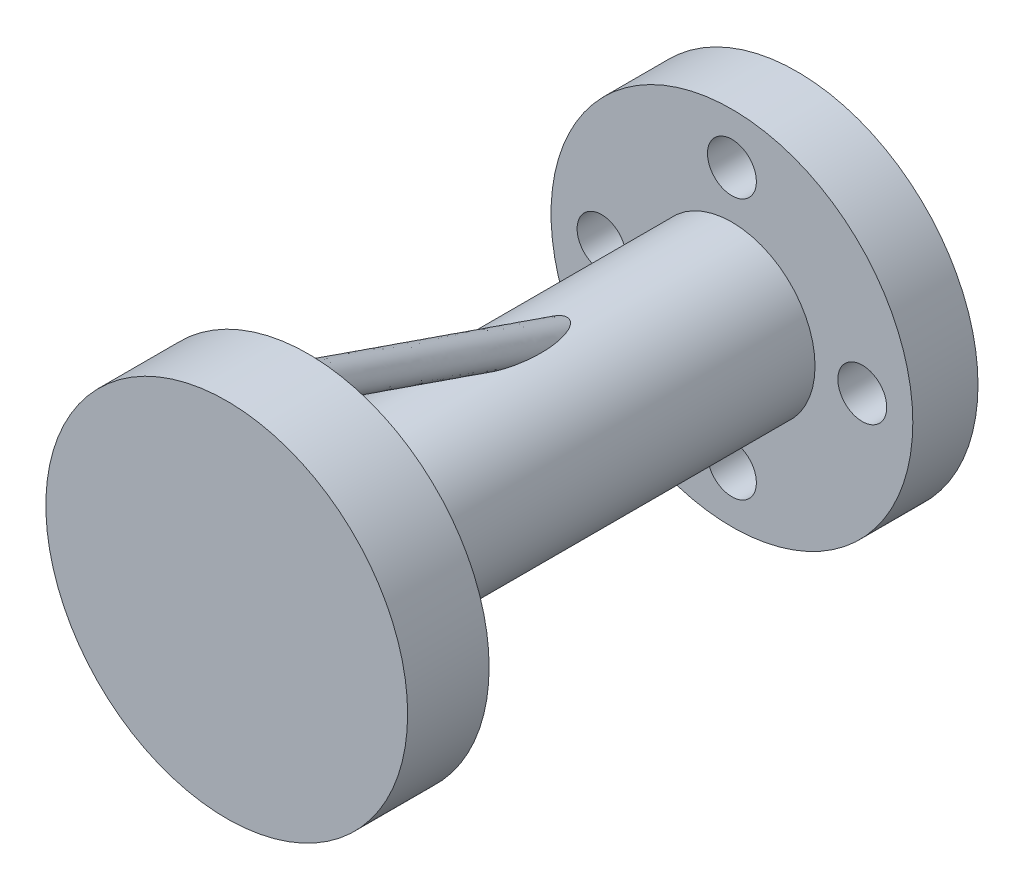
SolidWorks part; units mm, degrees
ref_plane "Front Plane" through (0, 0, 0) normal (0, 0, 1) x (1, 0, 0)
ref_plane "Top Plane" through (0, 0, 0) normal (0, 1, 0) x (1, 0, 0)
ref_plane "Right Plane" through (0, 0, 0) normal (1, 0, 0) x (0, 0, -1)
sketch "Sketch3" plane through (0, 0, 0) normal (0, 0, 1) x (1, 0, 0)
  circle A0 centre (0, 0) radius 11.1
  circle A2 centre (0, 0) radius 5.1
  circle A3 centre (0, 8) radius 1.5
  circle A4 centre (8, 0) radius 1.5
  circle A5 centre (0, -8) radius 1.5
  circle A6 centre (-8, 0) radius 1.5
  dimension "D1" = 4
extrude "Boss-Extrude5" add sketch "Sketch3" along normal blind 4
sketch "Sketch16" plane through (0, 0, 0) normal (0, 0, -1) x (-1, 0, 0)
  circle A0 centre (0, 0) radius 5.1
extrude "Boss-Extrude6" add sketch "Sketch16" against normal blind 30
sketch "Sketch17" plane through (0, 0, 30) normal (0, 0, 1) x (1, 0, 0)
  circle A0 centre (0, 0) radius 11.1
extrude "Boss-Extrude8" add sketch "Sketch17" along normal blind 5
sketch "Sketch19" plane through (0, 0, 30) normal (0, 0, -1) x (-1, 0, 0)
  line L0 (0, 11.1) -> (0, 5.1)
  line L1 (0, 5.1) -> (0, 8.1)
  line L2 (0, 8.1) -> (0, 11.1)
  line L3 (0, 9.6) -> (0, 8.1)
  circle A0 centre (0, 0) radius 11.1 construction
  circle A1 centre (0, 0) radius 5.1 construction
  circle A2 centre (0, 9.6) radius 1
sketch "Sketch20" plane through (0, 0, 0) normal (1, 0, 0) x (0, 0, -1)
  line L0 (-30, 9.6) -> (-12.9903, 3.712)
  line L1 (-30, 8.6) -> (-30, 10.6) construction
  line L4 (-12.9903, 3.712) -> (-30, 9.6)
  point P6 (0, 0)
sweep "Sweep1" add profiles "Sketch19" path "Sketch20"
